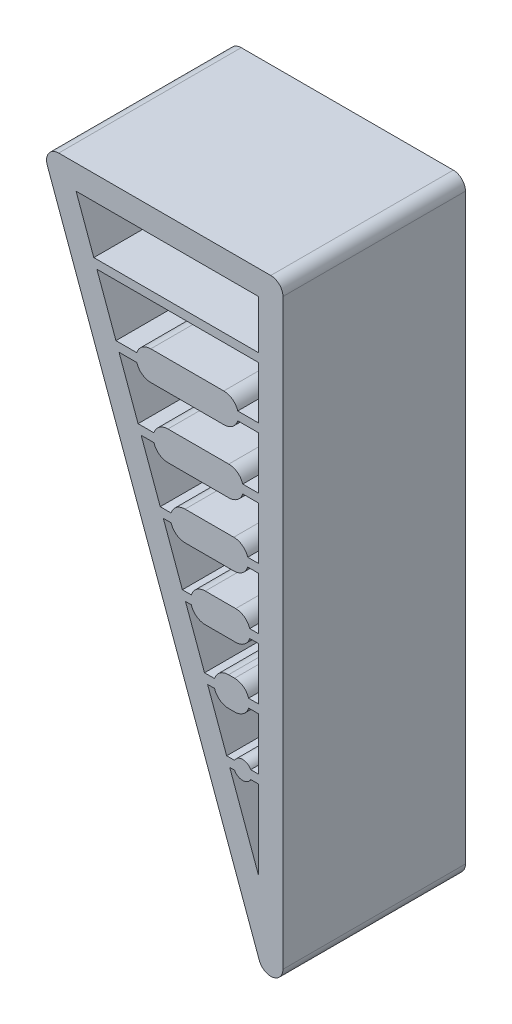
SolidWorks part; units mm, degrees
material "Custom Plastic"
ref_plane "Front Plane" through (0, 0, 0) normal (0, 0, 1) x (1, 0, 0)
ref_plane "Top Plane" through (0, 0, 0) normal (0, 1, 0) x (1, 0, 0)
ref_plane "Right Plane" through (0, 0, 0) normal (1, 0, 0) x (0, 0, -1)
sketch "Sketch1" plane through (0, 0, 0) normal (0, 0, 1) x (1, 0, 0)
  line L0 (0, 0) -> (-30, 0)
  line L1 (-30, 0) -> (-27.0882, -8)
  line L2 (0, -82.4243) -> (0, -69.4)
  line L3 (4, 4) -> (-35.7126, 4)
  line L4 (-35.7126, 4) -> (4, -105.1094)
  line L5 (4, -105.1094) -> (4, 4)
  line L6 (-27.0882, -8) -> (0, -8)
  line L7 (-26.5787, -9.4) -> (0, -9.4)
  line L8 (-23.4485, -18) -> (0, -18)
  line L9 (-22.939, -19.4) -> (0, -19.4)
  line L10 (-19.8088, -28) -> (0, -28)
  line L11 (-19.2993, -29.4) -> (0, -29.4)
  line L12 (-16.1691, -38) -> (0, -38)
  line L13 (-15.6596, -39.4) -> (0, -39.4)
  line L14 (-12.5294, -48) -> (0, -48)
  line L15 (-12.0199, -49.4) -> (0, -49.4)
  line L16 (-8.8897, -58) -> (0, -58)
  line L17 (-8.3802, -59.4) -> (0, -59.4)
  line L18 (-5.25, -68) -> (0, -68)
  line L19 (-4.7405, -69.4) -> (0, -69.4)
  line L20 (-26.5787, -9.4) -> (-23.4485, -18)
  line L21 (-30, 0) -> (0, -82.4243) construction
  line L22 (-22.939, -19.4) -> (-19.8088, -28)
  line L23 (-19.2993, -29.4) -> (-16.1691, -38)
  line L24 (-15.6596, -39.4) -> (-12.5294, -48)
  line L25 (-12.0199, -49.4) -> (-8.8897, -58)
  line L26 (-8.3802, -59.4) -> (-5.25, -68)
  line L27 (-4.7405, -69.4) -> (0, -82.4243)
  line L28 (0, -68) -> (0, -59.4)
  line L29 (0, -82.4243) -> (0, 0) construction
  line L30 (0, -58) -> (0, -49.4)
  line L31 (0, -48) -> (0, -39.4)
  line L32 (0, -38) -> (0, -29.4)
  line L33 (0, -28) -> (0, -19.4)
  line L34 (0, -18) -> (0, -9.4)
  line L35 (0, -8) -> (0, 0)
  point P31 (0, 0)
  dimension "D1" = 70
  dimension "D2" = 30
  dimension "D4" = 8
  dimension "D5" = 1.4
  dimension "D6" = 7
  dimension "D7" = 10
  dimension "D3" = 4
extrude "Boss-Extrude2" add sketch "Sketch1" along normal blind 30
fillet "Fillet2" radius 2 3 edges at (4, 4, 15) (-35.7126, 4, 15) (4, -105.1094, 15)
sketch "Sketch2" plane through (0, 0, 30) normal (0, 0, 1) x (1, 0, 0)
  line L0 (4, 2) -> (-34.8563, 2) construction
  line L1 (4, -93.7669) -> (4, 2) construction
  line L2 (2, 4) -> (-32.8563, 4) construction
  arc A0 (-32.8563, 4) -> (-34.7357, 1.316) centre (-32.8563, 2) ccw construction
  dimension "D1" = 2
sketch "Sketch4" plane through (0, 0, 30) normal (0, 0, 1) x (1, 0, 0)
  line L0 (-9.9044, -28) -> (-9.9044, -29.4) construction
  line L1 (-19.8088, -28) -> (0, -28) construction
  line L2 (-19.2993, -29.4) -> (0, -29.4) construction
  line L3 (-14.9044, -28.7) -> (-4.9044, -28.7) construction
  line L4 (-14.9044, -28.7) -> (-4.9044, -28.7) construction
  line L5 (-14.9044, -26.3) -> (-4.9044, -26.3)
  line L6 (-14.9044, -31.1) -> (-4.9044, -31.1)
  line L7 (-8.0846, -38) -> (-8.0846, -39.4) construction
  line L8 (-16.1691, -38) -> (0, -38) construction
  line L9 (-15.6596, -39.4) -> (0, -39.4) construction
  line L10 (-6.2647, -48) -> (-6.2647, -49.4) construction
  line L11 (-12.5294, -48) -> (0, -48) construction
  line L12 (-12.0199, -49.4) -> (0, -49.4) construction
  line L13 (-4.4449, -58) -> (-4.4449, -59.4) construction
  line L14 (-8.8897, -58) -> (0, -58) construction
  line L15 (-8.3802, -59.4) -> (0, -59.4) construction
  line L16 (-12.0846, -38.7) -> (-4.0846, -38.7) construction
  line L17 (-8.7647, -48.7) -> (-3.7647, -48.7) construction
  line L18 (-4.0846, -38.7) -> (-12.0846, -38.7) construction
  line L21 (-4.0846, -41.1) -> (-12.0846, -41.1)
  line L22 (-4.9449, -58.7) -> (-3.9449, -58.7) construction
  line L23 (-8.7647, -48.7) -> (-3.7647, -48.7) construction
  line L24 (-8.7647, -46.3) -> (-3.7647, -46.3)
  line L25 (-8.7647, -51.1) -> (-3.7647, -51.1)
  line L26 (-4.9449, -58.7) -> (-3.9449, -58.7) construction
  line L27 (-4.9449, -56.3) -> (-3.9449, -56.3)
  line L28 (-4.9449, -61.1) -> (-3.9449, -61.1)
  line L29 (-4.0846, -36.3) -> (-12.0846, -36.3)
  line L32 (-11.7243, -18) -> (-11.7243, -19.4) construction
  line L33 (-23.4485, -18) -> (0, -18) construction
  line L34 (-22.939, -19.4) -> (0, -19.4) construction
  line L35 (-5.7243, -18.7) -> (-17.7243, -18.7) construction
  line L36 (-5.7243, -18.7) -> (-17.7243, -18.7) construction
  line L37 (-5.7243, -21.1) -> (-17.7243, -21.1)
  line L38 (-5.7243, -16.3) -> (-17.7243, -16.3)
  arc A0 (-14.9044, -26.3) -> (-14.9044, -31.1) centre (-14.9044, -28.7) ccw
  arc A1 (-4.9044, -31.1) -> (-4.9044, -26.3) centre (-4.9044, -28.7) ccw
  arc A2 (-8.7647, -46.3) -> (-8.7647, -51.1) centre (-8.7647, -48.7) ccw
  arc A3 (-3.7647, -51.1) -> (-3.7647, -46.3) centre (-3.7647, -48.7) ccw
  arc A4 (-4.9449, -56.3) -> (-4.9449, -61.1) centre (-4.9449, -58.7) ccw
  arc A5 (-3.9449, -61.1) -> (-3.9449, -56.3) centre (-3.9449, -58.7) ccw
  arc A8 (-4.0846, -41.1) -> (-4.0846, -36.3) centre (-4.0846, -38.7) ccw
  arc A9 (-12.0846, -36.3) -> (-12.0846, -41.1) centre (-12.0846, -38.7) ccw
  arc A10 (-5.7243, -21.1) -> (-5.7243, -16.3) centre (-5.7243, -18.7) ccw
  arc A11 (-17.7243, -16.3) -> (-17.7243, -21.1) centre (-17.7243, -18.7) ccw
  point P6 (-9.9044, -28.7)
  point P9 (-9.9044, -28.7)
  point P32 (-8.0846, -38.7)
  point P35 (-8.0846, -38.7)
  point P38 (-6.2647, -48.7)
  point P44 (-6.2647, -48.7)
  point P51 (-4.4449, -58.7)
  point P55 (-4.4449, -58.7)
  point P62 (-11.7243, -18.7)
  point P65 (-11.7243, -18.7)
  dimension "D2" = 2.4
  dimension "D1" = 10
  dimension "D3" = 8
  dimension "D4" = 5
  dimension "D5" = 1
  dimension "D6" = 12
extrude "Boss-Extrude3" add sketch "Sketch4" against normal up to surface (30 mm away) up to face at (-14.2721, -4, 0)
sketch "Sketch5" plane through (0, 0, 30) normal (0, 0, 1) x (1, 0, 0)
  line L0 (-2.625, -68) -> (-2.625, -69.4) construction
  line L1 (-5.25, -68) -> (0, -68) construction
  line L2 (-4.7405, -69.4) -> (0, -69.4) construction
  circle A0 centre (-2.625, -68.7) radius 1.5
  dimension "D1" = 3
extrude "Boss-Extrude4" add sketch "Sketch5" against normal up to surface (30 mm away) up to face at (-12.1155, -15.3303, 0)
